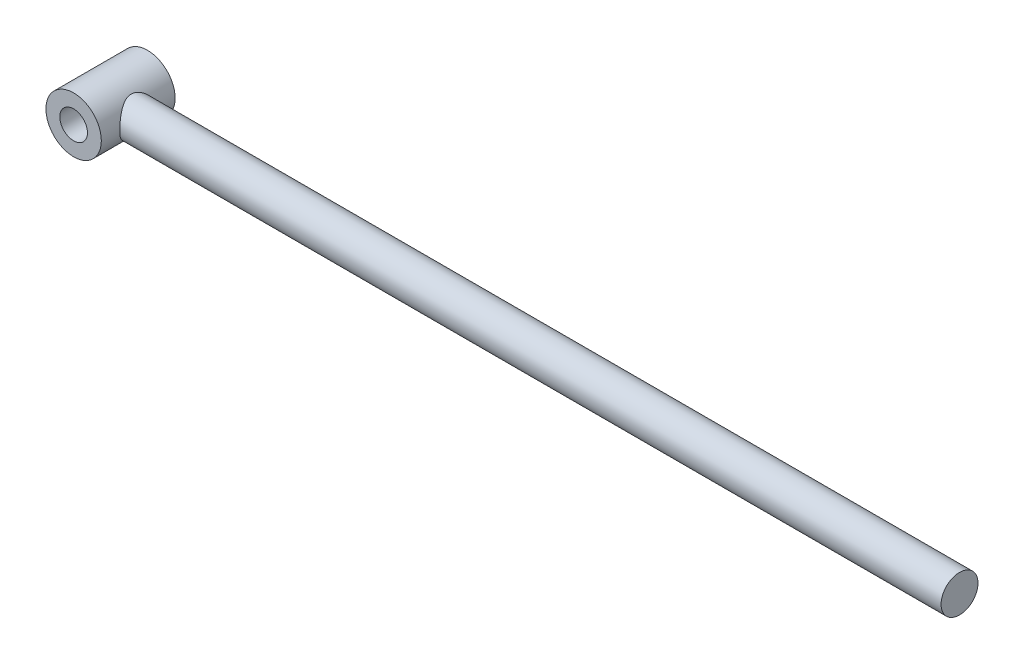
SolidWorks part; units mm, degrees
ref_plane "Front Plane" through (0, 0, 0) normal (0, 0, 1) x (1, 0, 0)
ref_plane "Top Plane" through (0, 0, 0) normal (0, 1, 0) x (1, 0, 0)
ref_plane "Right Plane" through (0, 0, 0) normal (1, 0, 0) x (0, 0, -1)
sketch "Sketch1" plane through (0, 0, 0) normal (0, 0, 1) x (1, 0, 0)
  circle A0 centre (0, 0) radius 30
  circle A1 centre (0, 0) radius 15
  dimension "D1" = 15
  dimension "D2" = 30
extrude "Boss-Extrude1" add sketch "Sketch1" along normal mid plane 80
ref_plane "Plane1" through (20, 0, 0) normal (1, 0, 0) x (0, 0, -1)
sketch "Sketch2" plane through (20, 0, 0) normal (1, 0, 0) x (0, 0, -1)
  circle A0 centre (0, 0) radius 20
  dimension "D1" = 40
extrude "Boss-Extrude2" add sketch "Sketch2" along normal blind 900
